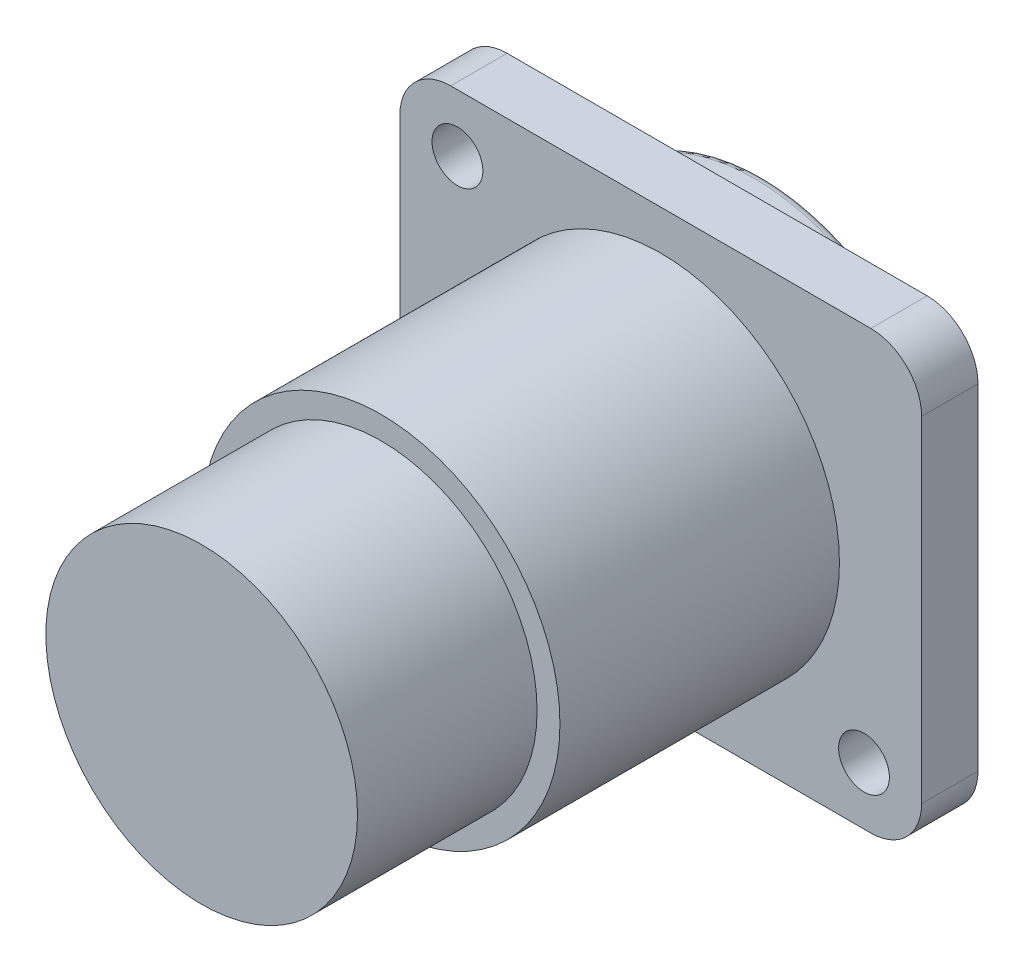
SolidWorks part; units mm, degrees
ref_plane "Płaszczyzna przednia" through (0, 0, 0) normal (0, 0, 1) x (1, 0, 0)
ref_plane "Płaszczyzna górna" through (0, 0, 0) normal (0, 1, 0) x (1, 0, 0)
ref_plane "Płaszczyzna prawa" through (0, 0, 0) normal (1, 0, 0) x (0, 0, -1)
sketch "Szkic1" plane through (0, 0, 0) normal (0, 0, 1) x (1, 0, 0)
  circle A0 centre (0, 0) radius 11.6
  dimension "D1" = 23.2
extrude "Dodanie-wyciągnięcie1" add sketch "Szkic1" along normal blind 2.7
fillet "Zaokrąglenie1" radius 0.5 1 edges at (11.6, 0, 0)
sketch "Szkic2" plane through (0, 0, 2.7) normal (0, 0, 1) x (1, 0, 0)
  line L1 (-15.4, -12.9) -> (15.4, -12.9)
  line L2 (-15.4, -12.9) -> (-15.4, 12.9)
  line L3 (-15.4, 12.9) -> (15.4, 12.9)
  line L4 (15.4, -12.9) -> (15.4, 12.9)
  line L5 (-15.4, -12.9) -> (15.4, 12.9) construction
  line L6 (-15.4, 12.9) -> (15.4, -12.9) construction
  point P0 (0, 0)
  dimension "D1" = 30.8
  dimension "D2" = 25.8
extrude "Dodanie-wyciągnięcie2" add sketch "Szkic2" along normal blind 3.33
sketch "Szkic3" plane through (0, 0, 6.03) normal (0, 0, 1) x (1, 0, 0)
  circle A0 centre (0, 0) radius 10.55
  dimension "D1" = 21.1
extrude "Dodanie-wyciągnięcie3" add sketch "Szkic3" along normal blind 16.5
sketch "Szkic4" plane through (0, 0, 22.53) normal (0, 0, 1) x (1, 0, 0)
  circle A0 centre (0, 0) radius 9.2
  dimension "D1" = 18.4
extrude "Dodanie-wyciągnięcie4" add sketch "Szkic4" along normal blind 10.6
sketch "Szkic5" plane through (0, 0, 2.7) normal (0, 0, -1) x (-1, 0, 0)
  line L0 (15.4, 12.9) -> (15.4, -12.9) construction
  line L1 (-15.4, -12.9) -> (-15.4, 12.9) construction
  line L2 (15.4, -12.9) -> (-15.4, -12.9) construction
  line L3 (-15.4, 12.9) -> (15.4, 12.9) construction
  circle A0 centre (-12, -9.5) radius 1.5
  circle A1 centre (12, 9.5) radius 1.5
  dimension "D1" = 3
  dimension "D4" = 3
  dimension "D6" = 3.4
  dimension "D2" = 3.4
  dimension "D3" = 3.4
  dimension "D5" = 3.4
extrude "Wytnij-wyciągnięcie1" cut sketch "Szkic5" against normal blind 10.6
fillet "Zaokrąglenie2" radius 3 4 edges at (15.4, 12.9, 4.365) (-15.4, 12.9, 4.365) (-15.4, -12.9, 4.365) (15.4, -12.9, 4.365)
